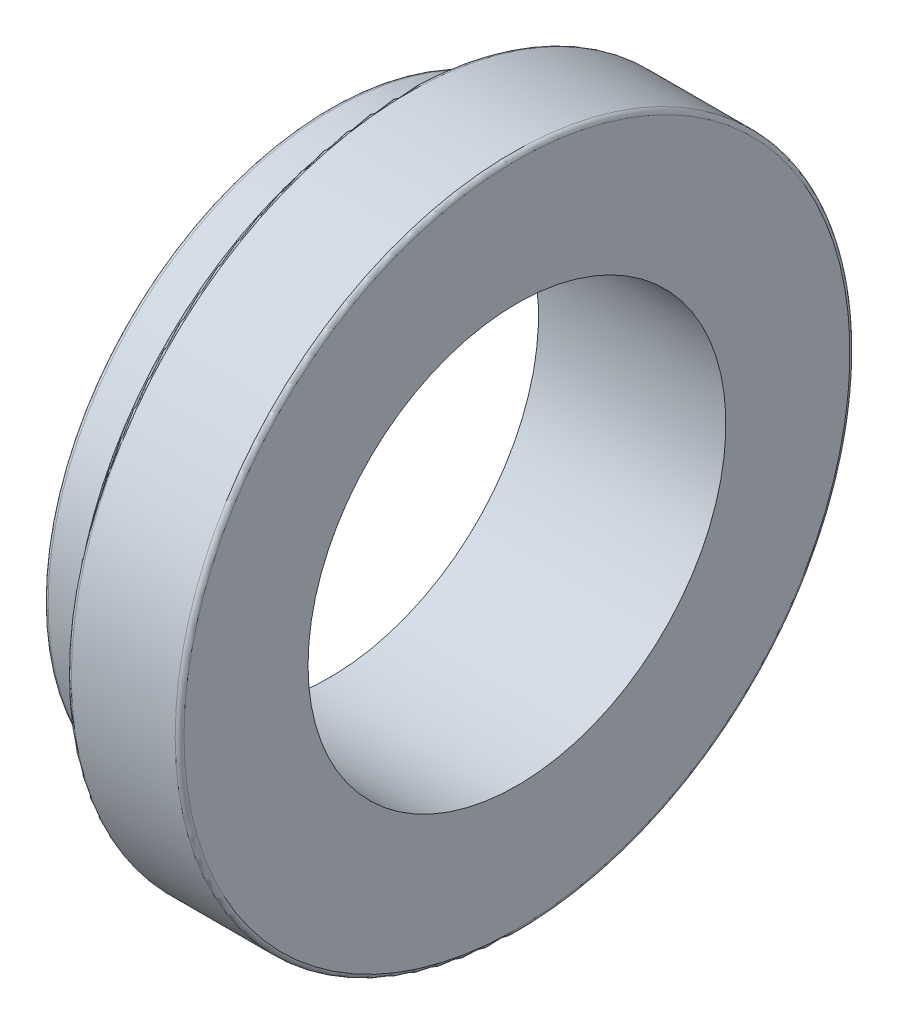
SolidWorks part; units mm, degrees
material "CD4Mc-U Duplex Stainless Steel"
ref_plane "Front Plane" through (0, 0, 0) normal (0, 0, 1) x (1, 0, 0)
ref_plane "Top Plane" through (0, 0, 0) normal (0, 1, 0) x (1, 0, 0)
ref_plane "Right Plane" through (0, 0, 0) normal (1, 0, 0) x (0, 0, -1)
sketch "Sketch1" plane through (0, 0, 0) normal (0, 0, 1) x (1, 0, 0)
  line L0 (0, 0) -> (79.6085, 0) construction
  line L3 (1.7959, 30.1625) -> (1.7959, 40.64)
  line L4 (2.4309, 41.275) -> (10.6859, 41.275)
  line L6 (10.9399, 46.0375) -> (12.3247, 46.0375)
  line L7 (12.5787, 46.2915) -> (12.5787, 48.0695)
  line L8 (13.2137, 48.7045) -> (28.2119, 48.7045)
  line L9 (28.8469, 48.0695) -> (28.8469, 30.1625)
  line L10 (28.8469, 30.1625) -> (1.7959, 30.1625)
  line L11 (10.6859, 45.7835) -> (10.6859, 41.275)
  arc A2 (12.5787, 48.0695) -> (13.2137, 48.7045) centre (13.2137, 48.0695) cw
  arc A3 (28.2119, 48.7045) -> (28.8469, 48.0695) centre (28.2119, 48.0695) cw
  arc A5 (1.7959, 40.64) -> (2.4309, 41.275) centre (2.4309, 40.64) cw
  arc A7 (12.3247, 46.0375) -> (12.5787, 46.2915) centre (12.3247, 46.2915) ccw
  arc A8 (10.9399, 46.0375) -> (10.6859, 45.7835) centre (10.9399, 45.7835) ccw
  dimension "D5" = 46.0375
  dimension "D7" = 0.254
  dimension "D1" = 48.7045
  dimension "D2" = 8.89
  dimension "D3" = 18.161
  dimension "D4" = 41.275
  dimension "D6" = 30.1625
revolve "Revolve1" add sketch "Sketch1" angle 360 about L0
